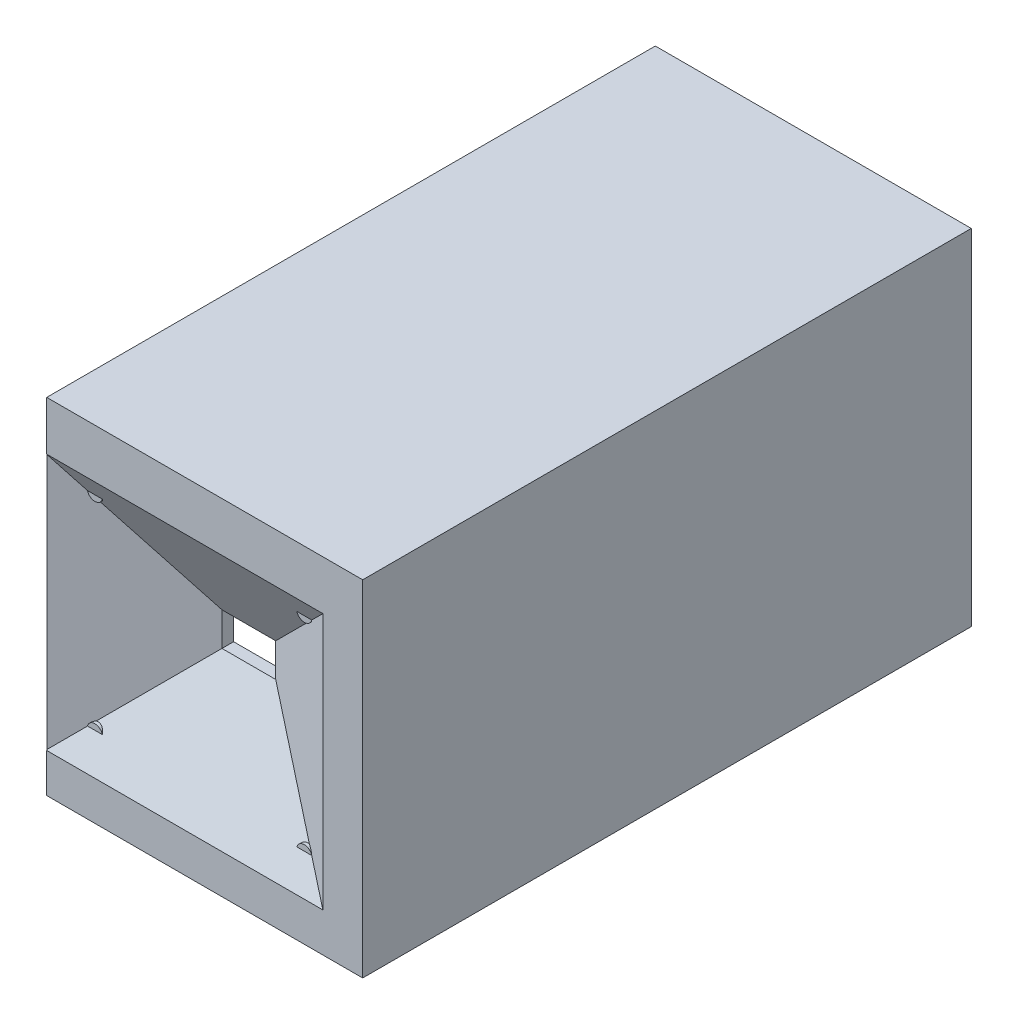
SolidWorks part; units mm, degrees
ref_plane "Front Plane" through (0, 0, 0) normal (0, 0, 1) x (1, 0, 0)
ref_plane "Top Plane" through (0, 0, 0) normal (0, 1, 0) x (1, 0, 0)
ref_plane "Right Plane" through (0, 0, 0) normal (1, 0, 0) x (0, 0, -1)
sketch "Sketch1" plane through (0, 0, 0) normal (0, 0, 1) x (1, 0, 0)
  line L10 (0, 0) -> (13.075, 0)
  line L15 (-13.575, -13.5) -> (-13.575, 13.5)
  line L16 (-13.575, 13.5) -> (13.575, 13.5)
  line L21 (13.575, -13.5) -> (13.575, 13.5)
  line L22 (-13.575, -13.5) -> (13.575, -13.5)
  line L28 (-12.425, -3.5) -> (-12.425, 3.5)
  line L29 (-12.425, 3.5) -> (-7.125, 3.5)
  line L30 (-7.125, -3.5) -> (-7.125, 3.5)
  line L31 (-12.425, -3.5) -> (-7.125, -3.5)
  line L32 (12.425, -3.5) -> (7.125, -3.5)
  line L33 (7.125, -3.5) -> (7.125, 3.5)
  line L34 (12.425, -3.5) -> (12.425, 3.5)
  line L35 (12.425, 3.5) -> (7.125, 3.5)
  line L36 (-2.65, -1.65) -> (-2.65, 1.65)
  line L37 (-2.65, 1.65) -> (2.65, 1.65)
  line L38 (2.65, -1.65) -> (2.65, 1.65)
  line L39 (-2.65, -1.65) -> (2.65, -1.65)
  circle A5 centre (10.325, 10.25) radius 0.762
  circle A6 centre (10.325, -10.25) radius 0.762
  circle A7 centre (-10.325, -10.25) radius 0.762
  circle A8 centre (-10.325, 10.25) radius 0.762
  point P0 (0, 0)
  point P16 (0, 0)
  point P31 (-9.775, 0)
  dimension "D10" = 1.524
  dimension "D11" = 1.524
  dimension "D12" = 1.524
  dimension "D13" = 1.524
  dimension "D18" = 13.075
ref_plane "Plane1" through (0, 0, 0) normal (0, 0, 1) x (1, 0, 0)
sketch "Sketch2" plane through (0, 0, 0) normal (0, 0, 1) x (1, 0, 0)
  line L0 (-16.575, 16.5) -> (-16.575, -16.5)
  line L5 (-16.575, -16.5) -> (16.575, -16.5)
  line L6 (16.575, 16.5) -> (16.575, -16.5)
  line L7 (-16.575, 16.5) -> (16.575, 16.5)
extrude "Boss-Extrude1" add sketch "Sketch2" along normal blind 7.5
ref_plane "Plane2" through (0, 0, 0) normal (0, 0, 1) x (1, 0, 0)
sketch "Sketch3" plane through (0, 0, 0) normal (0, 0, 1) x (1, 0, 0)
  circle A0 centre (10.325, 10.25) radius 0.762
  circle A1 centre (-10.325, 10.25) radius 0.762
  circle A2 centre (10.325, -10.25) radius 0.762
  circle A3 centre (-10.325, -10.25) radius 0.762
  dimension "D1" = 1.524
  dimension "D2" = 1.524
  dimension "D3" = 1.524
  dimension "D4" = 1.524
extrude "Cut-Extrude1" cut sketch "Sketch3" along normal blind 6
ref_plane "Plane3" through (0, 0, 0) normal (0, 0, 1) x (1, 0, 0)
sketch "Sketch4" plane through (0, 0, 0) normal (0, 0, 1) x (1, 0, 0)
  line L1 (12.425, -3.5) -> (7.125, -3.5)
  line L2 (12.425, -3.5) -> (12.425, 3.5)
  line L3 (12.425, 3.5) -> (7.125, 3.5)
  line L4 (7.125, -3.5) -> (7.125, 3.5)
  line L5 (-7.125, -3.5) -> (-12.425, -3.5)
  line L6 (-7.125, -3.5) -> (-7.125, 3.5)
  line L7 (-7.125, 3.5) -> (-12.425, 3.5)
  line L8 (-12.425, -3.5) -> (-12.425, 3.5)
extrude "Cut-Extrude2" cut sketch "Sketch4" along normal blind 3.4
ref_plane "Plane4" through (0, 0, 0) normal (0, 0, 1) x (1, 0, 0)
sketch "Sketch5" plane through (0, 0, 0) normal (0, 0, 1) x (1, 0, 0)
  line L1 (8.5467, -12.7134) -> (-8.766, -12.7134)
  line L2 (8.5467, -12.7134) -> (8.5467, -10.9049)
  line L3 (8.5467, -10.9049) -> (-8.766, -10.9049)
  line L4 (-8.766, -12.7134) -> (-8.766, -10.9049)
extrude "Cut-Extrude3" cut sketch "Sketch5" along normal blind 2
ref_plane "Plane5" through (0, 0, 0) normal (0, 0, 1) x (1, 0, 0)
sketch "Sketch6" plane through (0, 0, 0) normal (0, 0, 1) x (1, 0, 0)
  line L1 (2.65, -1.65) -> (-2.65, -1.65)
  line L2 (2.65, -1.65) -> (2.65, 1.65)
  line L3 (2.65, 1.65) -> (-2.65, 1.65)
  line L4 (-2.65, -1.65) -> (-2.65, 1.65)
extrude "Cut-Extrude4" cut sketch "Sketch6" along normal through all
chamfer "Chamfer3" distance 11 angle 30 4 edges at (-2.65, 0, 7.5) (0, -1.65, 7.5) (2.65, 0, 7.5) (0, 1.65, 7.5)
ref_plane "Plane7" through (0, 0, 0) normal (0, 0, 1) x (1, 0, 0)
sketch "Sketch7" plane through (0, 0, 0) normal (0, 0, 1) x (1, 0, 0)
  line L0 (16.575, 16.5) -> (-16.575, 16.5) construction
  line L1 (16.575, -16.5) -> (13.575, -16.5)
  line L3 (16.575, 16.5) -> (13.575, 16.5)
  line L4 (13.575, -16.5) -> (13.575, 16.5)
  line L5 (16.575, 16.5) -> (17.575, 16.5)
  line L6 (13.575, 13.5) -> (-16.575, 13.5)
  line L7 (13.575, 13.5) -> (13.575, 16.5)
  line L8 (13.575, 16.5) -> (-16.575, 16.5)
  line L9 (-16.575, 13.5) -> (-16.575, 16.5)
  line L10 (-13.575, 13.5) -> (-16.575, 13.5)
  line L11 (-13.575, 13.5) -> (-13.575, -16.5)
  line L12 (-13.575, -16.5) -> (-16.575, -16.5)
  line L13 (-16.575, 13.5) -> (-16.575, -16.5)
  line L14 (17.575, 16.5) -> (17.575, -16.5)
  line L15 (17.575, -16.5) -> (16.575, -16.5)
  dimension "D1" = 3
  dimension "D2" = 1
extrude "Boss-Extrude2" add sketch "Sketch7" against normal blind 52.5
sketch "Sketch8" plane through (0, 16.5, 0) normal (0, 1, 0) x (1, 0, 0)
  line L1 (-16.575, -7.5) -> (16.575, -7.5)
  line L2 (-16.575, -7.5) -> (-16.575, 52.5)
  line L3 (-16.575, 52.5) -> (16.575, 52.5)
  line L4 (16.575, -7.5) -> (16.575, 52.5)
extrude "Boss-Extrude3" add sketch "Sketch8" along normal blind 1
sketch "Sketch9" plane through (0, 0, -52.5) normal (0, 0, -1) x (-1, 0, 0)
  line L1 (13.575, -16.5) -> (16.575, -16.5)
  line L2 (13.575, -16.5) -> (13.575, 17.5)
  line L3 (13.575, 17.5) -> (16.575, 17.5)
  line L4 (16.575, -16.5) -> (16.575, 17.5)
extrude "Cut-Extrude5" cut sketch "Sketch9" against normal up to surface (60 mm away)
sketch "Sketch10" plane through (-13.575, 0, 0) normal (-1, 0, 0) x (0, 0, 1)
  line L0 (7.5, 17.5) -> (-52.5, 17.5) construction
  line L1 (-52.5, 17.5) -> (-52.5, 13.5) construction
  line L2 (7.5, -16.5) -> (0, -16.5) construction
  line L4 (7.5, 12.65) -> (7.5, 17.5) construction
  circle A0 centre (-44, 15.5) radius 0.762
  circle A1 centre (5, 11) radius 0.762
  circle A2 centre (5, -10) radius 0.762
  point P8 (0, 0)
  point P9 (0, 0)
  dimension "D2" = 1.524
  dimension "D1" = 2
  dimension "D3" = 8.5
  dimension "D4" = 6.5
  dimension "D5" = 6.5
  dimension "D6" = 2.5
extrude "Cut-Extrude6" cut sketch "Sketch10" against normal blind 6
sketch "Sketch11" plane through (0, -16.5, 0) normal (0, -1, 0) x (-1, 0, 0)
  line L0 (-16.575, -7.5) -> (-16.575, 0) construction
  line L1 (-17.575, 52.5) -> (-13.575, 52.5) construction
  line L2 (-16.575, -3.75) -> (5.2939, -3.75) construction
  line L4 (13.575, -7.5) -> (13.575, 0) construction
  line L5 (-17.575, 52.5) -> (-17.575, 0) construction
  line L6 (13.575, -7.5) -> (-16.575, -7.5) construction
  circle A0 centre (-15.575, 44) radius 0.762
  circle A1 centre (-15.575, -51.5) radius 0.762
  circle A2 centre (7.075, -4.5) radius 0.762
  circle A3 centre (-11.075, -4.5) radius 0.762
  dimension "D1" = 1.524
  dimension "D5" = 1.524
  dimension "D6" = 1.524
  dimension "D2" = 1
  dimension "D3" = 8.5
  dimension "D4" = 6.5
  dimension "D7" = 6.5
  dimension "D8" = 3
extrude "Cut-Extrude7" cut sketch "Sketch11" against normal blind 6
sketch "Sketch12" plane through (0, 0, -52.5) normal (0, 0, -1) x (-1, 0, 0)
  line L0 (-16.575, 17.5) -> (13.575, 17.5) construction
  line L2 (-17.575, -16.5) -> (-13.575, -16.5) construction
  line L3 (13.575, 17.5) -> (13.575, 13.5) construction
  line L4 (-17.575, 16.5) -> (-17.575, -16.5) construction
  circle A0 centre (-15.575, 15.5) radius 0.762
  circle A1 centre (-15.575, -14.5) radius 0.762
  circle A2 centre (11.575, 15.5) radius 0.762
  point P12 (0, 0)
  dimension "D3" = 1.524
  dimension "D6" = 1.524
  dimension "D7" = 1.524
  dimension "D1" = 2
  dimension "D2" = 2
  dimension "D4" = 2
  dimension "D5" = 2
  dimension "D8" = 2
  dimension "D9" = 2
extrude "Cut-Extrude9" cut sketch "Sketch12" against normal blind 7
sketch "Sketch13" plane through (13.575, 0, 0) normal (-1, 0, 0) x (0, 0, 1)
  line L0 (-52.5, -16.5) -> (-52.5, 13.5) construction
  line L1 (-52.5, 7) -> (-46.5, 7)
  line L2 (-52.5, 7) -> (-52.5, -13)
  line L3 (-52.5, -13) -> (-46.5, -13)
  line L4 (-46.5, 7) -> (-46.5, -13)
  line L5 (-52.5, -16.5) -> (0, -16.5) construction
  line L7 (-46.5, -13) -> (-43.5, -13)
  line L8 (-46.5, -13) -> (-46.5, -8)
  line L9 (-46.5, -8) -> (-43.5, -8)
  line L10 (-43.5, -13) -> (-43.5, -8)
  line M8 (-52.5, 13.5) -> (-52.5, -16.5)
  dimension "D1" = 3.5
  dimension "D2" = 20
  dimension "D3" = 6
  dimension "D4" = 3
  dimension "D5" = 5
extrude "Cut-Extrude10" cut sketch "Sketch13" against normal blind 1.5 contours L4 L1 L3 M8 | L7 L10 L9 L4
sketch "Sketch14" plane through (16.575, 0, 0) normal (1, 0, 0) x (0, 0, -1)
  line L0 (0, 17.1325) -> (0, -17.1325) construction
  line L1 (-7.5, 17.5) -> (0, 17.5)
  line L2 (-7.5, 17.5) -> (-7.5, -16.5)
  line L3 (-7.5, -16.5) -> (0, -16.5)
  line L4 (0, 17.5) -> (0, -16.5)
  line L5 (52.5, -16.5) -> (0, -16.5) construction
  line L6 (0, 16.5) -> (52.5, 16.5) construction
  line L7 (52.5, 17.5) -> (0, 17.5)
  line L8 (52.5, 17.5) -> (52.5, 16.5)
  line L9 (52.5, 16.5) -> (0, 16.5)
  line L10 (0, 17.5) -> (0, 16.5)
  line M1 (0, -16.5) -> (0, 16.5)
  line M2 (0, 16.5) -> (52.5, 16.5)
  line M3 (52.5, 16.5) -> (52.5, 17.5)
  line M4 (52.5, 17.5) -> (-7.5, 17.5)
  line M5 (-7.5, 17.5) -> (-7.5, -16.5)
  line M6 (-7.5, -16.5) -> (0, -16.5)
extrude "Boss-Extrude4" add sketch "Sketch14" along normal blind 1 contours L4 M4 M5 M6 M1 | L4 M4 M2 M3
sketch "Sketch15" plane through (0, 13.5, 0) normal (0, -1, 0) x (1, 0, 0)
  line L1 (-10.813, -6.776) -> (-10.813, -8.3) construction
  line L2 (-10.813, -8.3) -> (-11.575, -7.538) construction
  line L3 (-11.575, -7.538) -> (-10.051, -7.538) construction
  line L4 (17.1325, 0) -> (-17.1325, 0) construction
  line L5 (-13.575, -52.5) -> (-13.575, 0) construction
  line L6 (9.915, -22.458) -> (11.439, -22.458) construction
  line L7 (11.439, -22.458) -> (10.677, -21.696) construction
  line L8 (10.677, -21.696) -> (10.677, -23.22) construction
  line L9 (13.575, -52.5) -> (-13.575, -52.5) construction
  line L10 (13.575, -52.5) -> (13.575, 0) construction
  circle A0 centre (-10.813, -7.538) radius 0.762
  circle A1 centre (10.677, -22.458) radius 0.762
  dimension "D1" = 1.524
  dimension "D2" = 1.524
  dimension "D6" = 3.66
  dimension "D3" = 8.3
  dimension "D4" = 2
  dimension "D5" = 29.28
extrude "Cut-Extrude11" cut sketch "Sketch15" against normal blind 3.5
